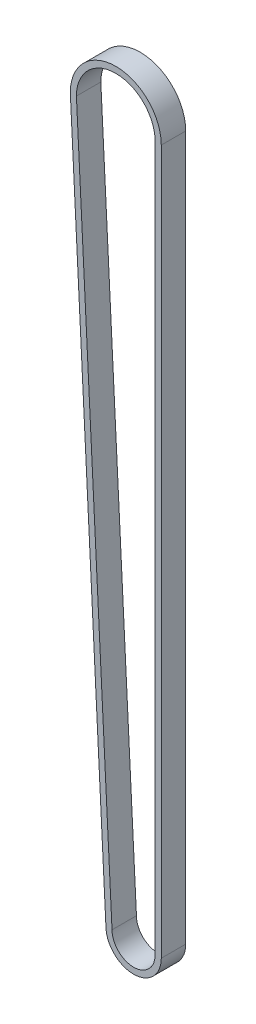
SolidWorks part; units mm, degrees
ref_plane "Plan de face" through (0, 0, 0) normal (0, 0, 1) x (1, 0, 0)
ref_plane "Plan de dessus" through (0, 0, 0) normal (0, 1, 0) x (1, 0, 0)
ref_plane "Plan de droite" through (0, 0, 0) normal (1, 0, 0) x (0, 0, -1)
sketch "Esquisse1" plane through (0, 0, 0) normal (0, 0, 1) x (1, 0, 0)
  line L0 (4.0417, 47.6402) -> (4.0417, -125.3598)
  line L1 (-15.3083, 47.6402) -> (-6.5583, -125.3598)
  line L2 (5.5417, 47.6402) -> (5.5417, -125.3598)
  line L3 (-16.8083, 47.6402) -> (-8.0583, -125.3598)
  arc A0 (4.0417, 47.6402) -> (-15.3083, 47.6402) centre (-5.6333, 47.6402) ccw
  arc A1 (-6.5583, -125.3598) -> (4.0417, -125.3598) centre (-1.2583, -125.3598) ccw
  arc A2 (5.5417, 47.6402) -> (-16.8083, 47.6402) centre (-5.6333, 47.6402) ccw
  arc A3 (-8.0583, -125.3598) -> (5.5417, -125.3598) centre (-1.2583, -125.3598) ccw
  dimension "D1" = 173
  dimension "D2" = 5.3
  dimension "D3" = 6.8
  dimension "D4" = 9.675
extrude "Extrusion1" add sketch "Esquisse1" along normal blind 6
